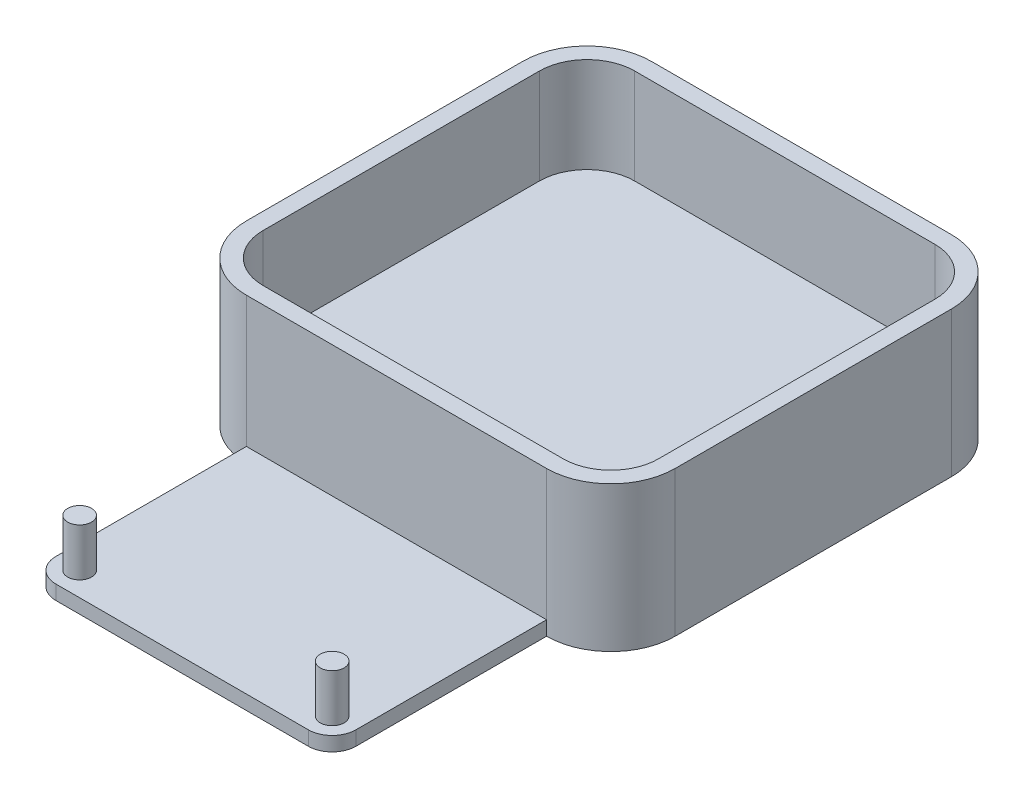
SolidWorks part; units mm, degrees
ref_plane "Front Plane" through (0, 0, 0) normal (0, 0, 1) x (1, 0, 0)
ref_plane "Top Plane" through (0, 0, 0) normal (0, 1, 0) x (1, 0, 0)
ref_plane "Right Plane" through (0, 0, 0) normal (1, 0, 0) x (0, 0, -1)
sketch "Sketch1" plane through (0, 0, 0) normal (0, 1, 0) x (1, 0, 0)
  line L1 (0, 85) -> (90, 85)
  line L2 (0, 85) -> (0, 0)
  line L3 (0, 0) -> (90, 0)
  line L4 (90, 85) -> (90, 0)
  line L5 (10, 50) -> (80, 50)
  line L6 (10, 50) -> (10, 30)
  line L7 (10, 30) -> (80, 30)
  line L8 (80, 50) -> (80, 30)
extrude "Boss-Extrude1" add sketch "Sketch1" along normal blind 7.5
sketch "Sketch2" plane through (0, 7.5, 0) normal (0, 1, 0) x (1, 0, 0)
  line L1 (0, 85) -> (90, 85)
  line L2 (0, 85) -> (0, 0)
  line L3 (0, 0) -> (90, 0)
  line L4 (90, 85) -> (90, 0)
extrude "Boss-Extrude2" add sketch "Sketch2" along normal blind 3
sketch "Sketch3" plane through (0, 10.5, 0) normal (0, 1, 0) x (1, 0, 0)
  line L1 (0, 85) -> (90, 85)
  line L2 (0, 85) -> (0, 0)
  line L3 (0, 0) -> (90, 0)
  line L4 (90, 85) -> (90, 0)
  line L5 (3.5, 3.5) -> (86.5, 3.5)
  line L6 (3.5, 3.5) -> (3.5, 81.5)
  line L7 (3.5, 81.5) -> (86.5, 81.5)
  line L8 (86.5, 3.5) -> (86.5, 81.5)
extrude "Boss-Extrude3" add sketch "Sketch3" along normal blind 20 contours L6 L5 L8 L7 | L2 L1 L4 L3
fillet "Fillet1" radius 10 1 edges at (3.5, 20.5, -81.5)
fillet "Fillet3" radius 10 1 edges at (86.5, 20.5, -81.5)
fillet "Fillet4" radius 10 1 edges at (3.5, 20.5, -3.5)
fillet "Fillet5" radius 10 1 edges at (86.5, 20.5, -3.5)
fillet "Fillet7" radius 13.5 1 edges at (0, 15.25, 0)
fillet "Fillet8" radius 13.5 1 edges at (90, 15.25, 0)
fillet "Fillet9" radius 13.5 1 edges at (90, 15.25, -85)
fillet "Fillet10" radius 13.5 1 edges at (0, 15.25, -85)
sketch "Sketch4" plane through (0, 0, 0) normal (0, -1, 0) x (1, 0, 0)
  line L1 (13.5, 0) -> (76.5, 0)
  line L2 (13.5, 0) -> (13.5, 45)
  line L3 (13.5, 45) -> (76.5, 45)
  line L4 (76.5, 0) -> (76.5, 45)
extrude "Boss-Extrude4" add sketch "Sketch4" against normal blind 3
fillet "Fillet15" radius 5 1 edges at (13.5, 1.5, 45)
fillet "Fillet16" radius 5 1 edges at (76.5, 1.5, 45)
sketch "Sketch7" plane through (0, 3, 0) normal (0, 1, 0) x (1, 0, 0)
  circle A0 centre (18.5, -40) radius 2.5
  circle A1 centre (71.5, -40) radius 2.5
extrude "Boss-Extrude6" add sketch "Sketch7" along normal blind 10
